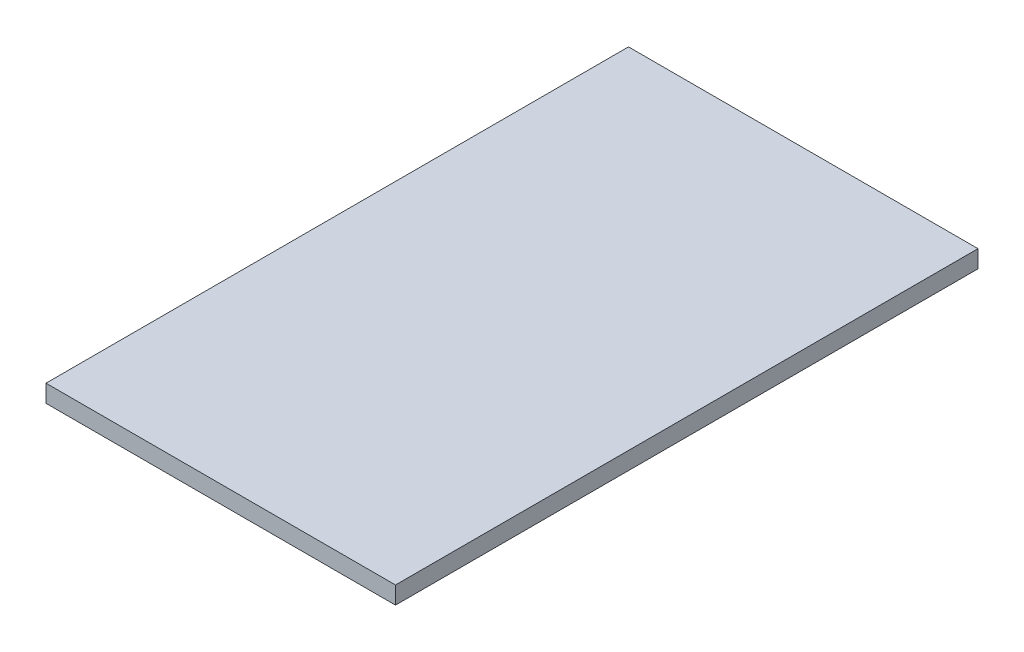
SolidWorks part; units mm, degrees
ref_plane "Front Plane" through (0, 0, 0) normal (0, 0, 1) x (1, 0, 0)
ref_plane "Top Plane" through (0, 0, 0) normal (0, 1, 0) x (1, 0, 0)
ref_plane "Right Plane" through (0, 0, 0) normal (1, 0, 0) x (0, 0, -1)
sketch "Sketch8" plane through (0, 0, 0) normal (0, 1, 0) x (1, 0, 0)
  line L1 (-300, 500) -> (300, 500)
  line L2 (-300, 500) -> (-300, -500)
  line L3 (-300, -500) -> (300, -500)
  line L4 (300, 500) -> (300, -500)
  line L5 (-300, 500) -> (300, -500) construction
  line L6 (-300, -500) -> (300, 500) construction
  point P0 (0, 0)
  dimension "D1" = 1000
  dimension "D2" = 600
extrude "Boss-Extrude9" add sketch "Sketch8" along normal blind 30
sketch "Sketch11" plane through (0, 0, 0) normal (0, 1, 0) x (1, 0, 0)
  circle A0 centre (0, 0) radius 5
  circle A1 centre (0, 0) radius 10
extrude "Boss-Extrude12" add sketch "Sketch11" along normal blind 10
sketch "Sketch12" plane through (0, 0, 0) normal (0, -1, 0) x (-1, 0, 0)
  circle A0 centre (0, 0) radius 10
extrude "Boss-Extrude13" add sketch "Sketch12" along normal blind 10
